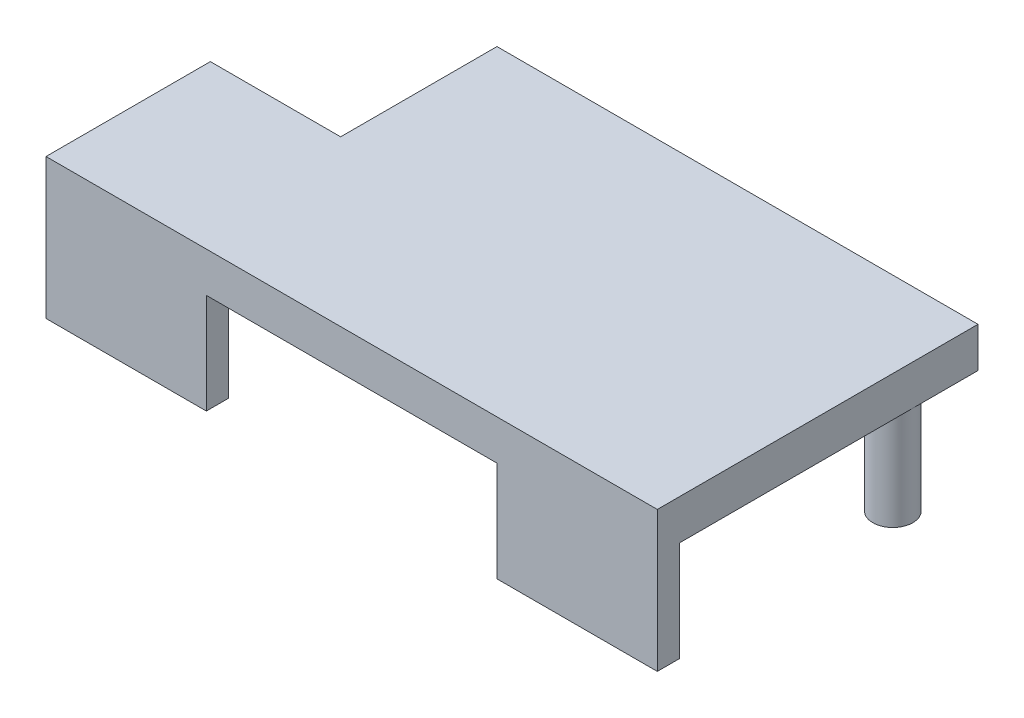
SolidWorks part; units mm, degrees
ref_plane "Ebene vorne" through (0, 0, 0) normal (0, 0, 1) x (1, 0, 0)
ref_plane "Ebene oben" through (0, 0, 0) normal (0, 1, 0) x (1, 0, 0)
ref_plane "Ebene rechts" through (0, 0, 0) normal (1, 0, 0) x (0, 0, -1)
sketch "Sketch1" plane through (0, 0, 0) normal (0, 1, 0) x (1, 0, 0)
  line L1 (-15.25, 8) -> (15.25, 8)
  line L2 (-15.25, 8) -> (-15.25, -8)
  line L3 (-15.25, -8) -> (15.25, -8)
  line L4 (15.25, 8) -> (15.25, -8)
  line L5 (-15.25, 8) -> (15.25, -8) construction
  line L6 (-15.25, -8) -> (15.25, 8) construction
  point P0 (0, 0)
  dimension "D1" = 16
  dimension "D2" = 30.5
extrude "Boss-Extrude1" add sketch "Sketch1" along normal blind 2
sketch "Sketch3" plane through (0, 0, 0) normal (0, 1, 0) x (1, 0, 0)
  line L0 (-9.3, 6.9) -> (-9.3, 2.7) construction
  line L1 (-15.7, 6.9) -> (-9.3, 6.9) construction
  line L2 (-15.7, 6.9) -> (-15.7, -6.9) construction
  line L3 (-15.7, -6.9) -> (15.7, -6.9) construction
  line L4 (15.7, 2.7) -> (15.7, -6.9) construction
  line L5 (-15.25, 8) -> (-15.25, -8) construction
  line L7 (-9.3, 2.7) -> (15.7, 2.7) construction
  line L11 (15.25, 8) -> (-15.25, 8) construction
  line L12 (-5.7, 8) -> (-2.8, 8)
  line L13 (-15.25, -8) -> (-7.25, -8)
  line L14 (-15.25, -8) -> (-15.25, -6.9)
  line L15 (-15.25, -6.9) -> (-7.25, -6.9)
  line L16 (-7.25, -8) -> (-7.25, -6.9)
  line L17 (15.25, -8) -> (7.25, -8)
  line L18 (15.25, -8) -> (15.25, -6.9)
  line L19 (15.25, -6.9) -> (7.25, -6.9)
  line L20 (7.25, -8) -> (7.25, -6.9)
  line L21 (-5.7, 8) -> (-5.7, 5.2)
  line L22 (-5.7, 5.2) -> (-2.8, 5.2)
  line L23 (-2.8, 8) -> (-2.8, 5.2)
  circle A0 centre (14.2, 4.8) radius 1
  point P0 (0, 0)
  point P4 (-15.25, 6.9)
  dimension "D5" = 2
  dimension "D1" = 13.8
  dimension "D2" = 31.4
  dimension "D3" = 25
  dimension "D4" = 9.6
  dimension "D6" = 1.1
  dimension "D7" = 8
  dimension "D8" = 8
  dimension "D9" = 1.1
  dimension "D12" = 9.55
  dimension "D13" = 2.9
  dimension "D14" = 2.8
extrude "Boss-Extrude3" add sketch "Sketch3" against normal blind 8
sketch "Sketch4" plane through (0, 0, 0) normal (0, 1, 0) x (1, 0, 0)
  line L0 (-15.25, 2.7) -> (-15.25, 8)
  line L2 (-15.25, 2.7) -> (-15.25, 0.2)
  line L3 (-15.25, 0.2) -> (-8.75, 0.2)
  line L4 (-8.75, 2.7) -> (-8.75, 0.2)
  line L11 (15.25, 8) -> (-15.25, 8) construction
  line L12 (-15.25, 8) -> (-8.75, 8)
  line L13 (-8.75, 8) -> (-8.75, 2.7)
  dimension "D1" = 6.5
extrude "Cut-Extrude2" cut sketch "Sketch4" along normal blind 10
sketch "Sketch5" plane through (0, -8, 0) normal (0, -1, 0) x (1, 0, 0)
  line L1 (-15.25, 8) -> (15.25, 8)
  line L2 (-15.25, 8) -> (-15.25, 6.9)
  line L3 (-15.25, 6.9) -> (15.25, 6.9)
  line L4 (15.25, 8) -> (15.25, 6.9)
  circle A0 centre (14.2, -4.8) radius 1
extrude "Cut-Extrude3" cut sketch "Sketch5" against normal blind 3
